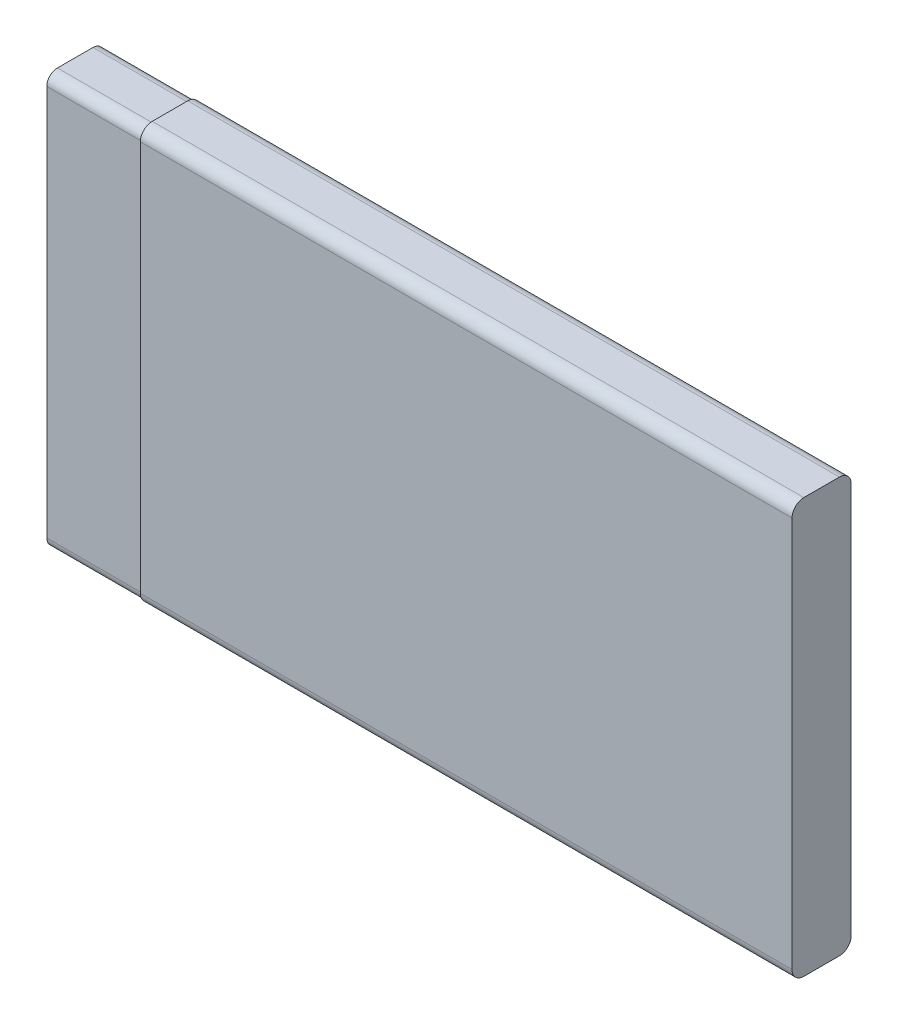
SolidWorks part; units mm, degrees
ref_plane "Front Plane" through (0, 0, 0) normal (0, 0, 1) x (1, 0, 0)
ref_plane "Top Plane" through (0, 0, 0) normal (0, 1, 0) x (1, 0, 0)
ref_plane "Right Plane" through (0, 0, 0) normal (1, 0, 0) x (0, 0, -1)
sketch "Sketch1" plane through (0, 0, 0) normal (0, 0, 1) x (1, 0, 0)
  line L1 (-31.5, 17.5) -> (31.5, 17.5) construction
  line L2 (-31.5, 17.5) -> (-31.5, -17.5) construction
  line L3 (-31.5, -17.5) -> (31.5, -17.5) construction
  line L4 (31.5, 17.5) -> (31.5, -17.5) construction
  line L5 (-31.5, 17.5) -> (31.5, -17.5) construction
  line L6 (-31.5, -17.5) -> (31.5, 17.5) construction
  line L7 (31.5, 17.5) -> (-23.5, 17.5)
  line L8 (31.5, 17.5) -> (31.5, -17.5)
  line L9 (31.5, -17.5) -> (-23.5, -17.5)
  line L10 (-23.5, 17.5) -> (-23.5, -17.5)
  point P0 (0, 0)
  dimension "D1" = 63
  dimension "D2" = 35
  dimension "D3" = 55
extrude "Boss-Extrude1" add sketch "Sketch1" along normal mid plane 5
fillet "Fillet1" radius 1 4 edges at (4, -17.5, 2.5) (4, -17.5, -2.5) (4, 17.5, -2.5) (4, 17.5, 2.5)
sketch "Sketch2" plane through (0, 0, 0) normal (0, 0, 1) x (1, 0, 0)
  line L1 (-29, 16.5) -> (-23.5, 16.5)
  line L2 (-29, 16.5) -> (-29, -16.5)
  line L3 (-29, -16.5) -> (-23.5, -16.5)
  line L4 (-23.5, 16.5) -> (-23.5, -16.5)
  line L5 (-31.5, -17.5) -> (31.5, -17.5) construction
  line L6 (-31.5, 17.5) -> (31.5, 17.5) construction
  point P4 (0, 0)
  point P7 (0, 0)
  point P8 (0, 0)
  point P9 (0, 0)
  point P13 (0, 0)
  dimension "D1" = 5.5
  dimension "D2" = 1
  dimension "D3" = 1
extrude "Boss-Extrude2" add sketch "Sketch2" along normal mid plane 1.6
sketch "Sketch3" plane through (-23.5, 0, 0) normal (-1, 0, 0) x (0, 0, 1)
  line L0 (-1.5, -17.4) -> (1.5, -17.4)
  line L1 (2.4, -16.5) -> (2.4, 16.5)
  line L2 (1.5, 17.4) -> (-1.5, 17.4)
  line L3 (-2.4, 16.5) -> (-2.4, -16.5)
  line L4 (-1.5, -17.5) -> (1.5, -17.5)
  line L5 (2.5, -16.5) -> (2.5, 16.5)
  line L6 (1.5, 17.5) -> (-1.5, 17.5)
  line L7 (-2.5, 16.5) -> (-2.5, -16.5)
  line L8 (-1.5, -17.5) -> (1.5, -17.5) construction
  line L9 (2.5, -16.5) -> (2.5, 16.5) construction
  line L10 (1.5, 17.5) -> (-1.5, 17.5) construction
  line L11 (-2.5, 16.5) -> (-2.5, -16.5) construction
  line L12 (-1.5, -17.3) -> (1.5, -17.3)
  line L13 (2.3, -16.5) -> (2.3, 16.5)
  line L14 (1.5, 17.3) -> (-1.5, 17.3)
  line L15 (-2.3, 16.5) -> (-2.3, -16.5)
  arc A0 (1.5, -17.4) -> (2.4, -16.5) centre (1.5, -16.5) ccw
  arc A1 (2.4, 16.5) -> (1.5, 17.4) centre (1.5, 16.5) ccw
  arc A2 (-1.5, 17.4) -> (-2.4, 16.5) centre (-1.5, 16.5) ccw
  arc A3 (-2.4, -16.5) -> (-1.5, -17.4) centre (-1.5, -16.5) ccw
  arc A4 (1.5, -17.5) -> (2.5, -16.5) centre (1.5, -16.5) ccw
  arc A5 (2.5, 16.5) -> (1.5, 17.5) centre (1.5, 16.5) ccw
  arc A6 (-1.5, 17.5) -> (-2.5, 16.5) centre (-1.5, 16.5) ccw
  arc A7 (-2.5, -16.5) -> (-1.5, -17.5) centre (-1.5, -16.5) ccw
  arc A8 (1.5, -17.5) -> (2.5, -16.5) centre (1.5, -16.5) ccw construction
  arc A9 (2.5, 16.5) -> (1.5, 17.5) centre (1.5, 16.5) ccw construction
  arc A10 (-1.5, 17.5) -> (-2.5, 16.5) centre (-1.5, 16.5) ccw construction
  arc A11 (-2.5, -16.5) -> (-1.5, -17.5) centre (-1.5, -16.5) ccw construction
  arc A12 (1.5, -17.3) -> (2.3, -16.5) centre (1.5, -16.5) ccw
  arc A13 (2.3, 16.5) -> (1.5, 17.3) centre (1.5, 16.5) ccw
  arc A14 (-1.5, 17.3) -> (-2.3, 16.5) centre (-1.5, 16.5) ccw
  arc A15 (-2.3, -16.5) -> (-1.5, -17.3) centre (-1.5, -16.5) ccw
  dimension "D1" = 0
  dimension "D2" = 0.1
  dimension "D3" = 0.1
extrude "Boss-Extrude4" add sketch "Sketch3" along normal up to vertex (8 mm away) up to point (-31.5, -17.5, 0)
